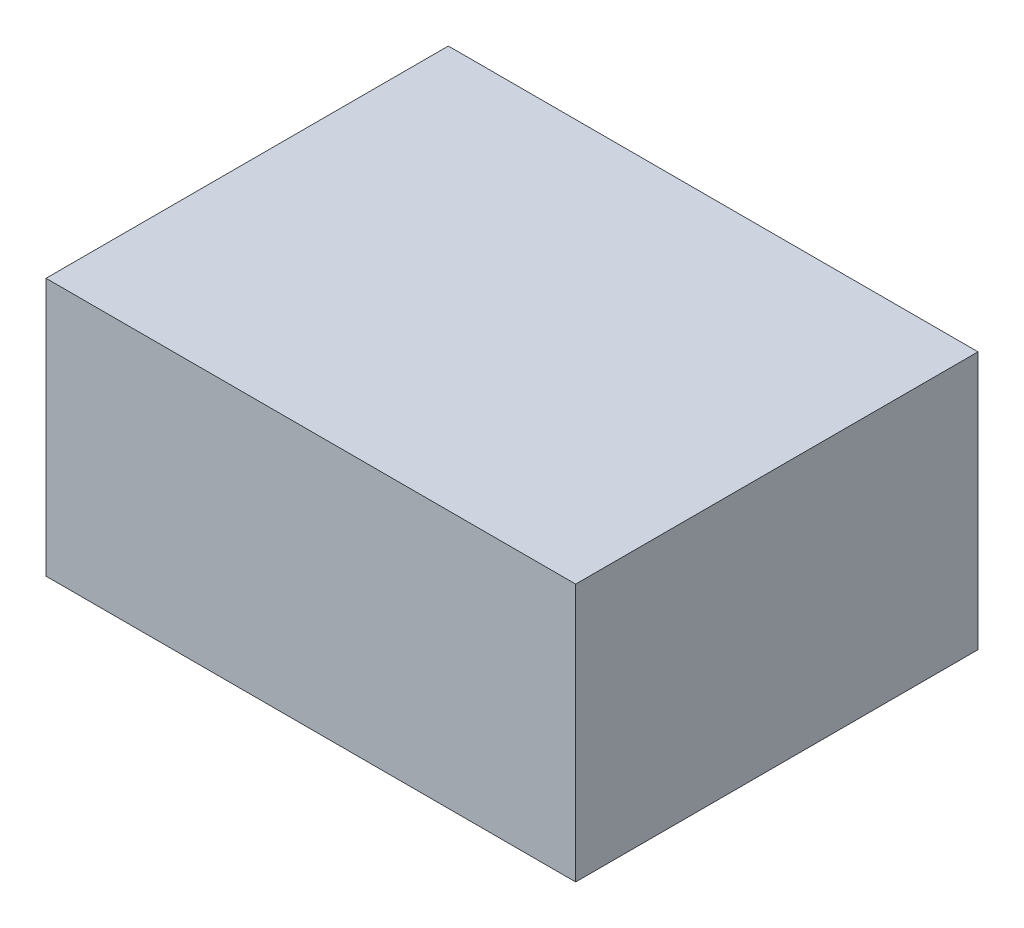
SolidWorks part; units mm, degrees
ref_plane "Plan de face" through (0, 0, 0) normal (0, 0, 1) x (1, 0, 0)
ref_plane "Plan de dessus" through (0, 0, 0) normal (0, 1, 0) x (1, 0, 0)
ref_plane "Plan de droite" through (0, 0, 0) normal (1, 0, 0) x (0, 0, -1)
sketch "Esquisse1" plane through (0, 0, 0) normal (0, 1, 0) x (1, 0, 0)
  line L0 (0, 0) -> (42.13, 0)
  line L1 (42.13, 0) -> (42.13, 32)
  line L2 (42.13, 32) -> (0, 32)
  line L3 (0, 32) -> (0, 0)
extrude "Boss.-Extru.1" add sketch "Esquisse1" along normal blind 20.52 contours L3 L0 L1 L2
